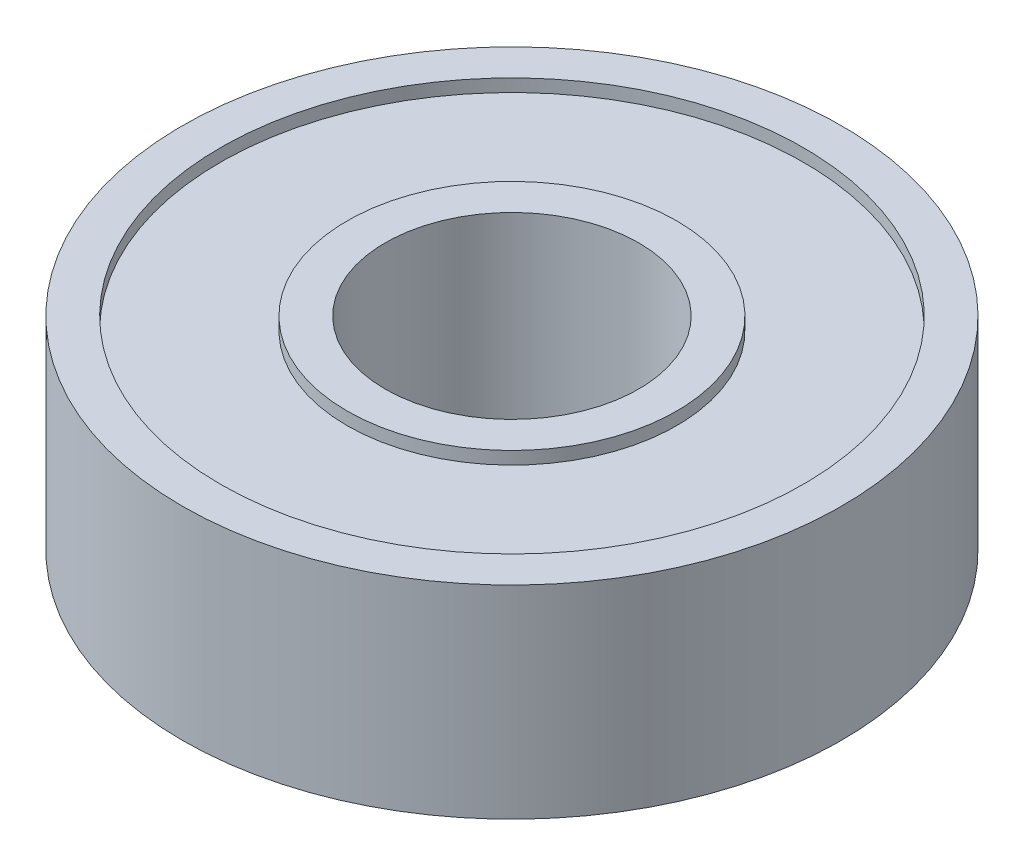
SolidWorks part; units mm, degrees
ref_plane "Plano frontal" through (0, 0, 0) normal (0, 0, 1) x (1, 0, 0)
ref_plane "Plano superior" through (0, 0, 0) normal (0, 1, 0) x (1, 0, 0)
ref_plane "Plano direito" through (0, 0, 0) normal (1, 0, 0) x (0, 0, -1)
sketch "Esboço1" plane through (0, 0, 0) normal (0, 0, 1) x (1, 0, 0)
  line L0 (0, 7.6011) -> (0, -6.5883) construction
  line L1 (5, 4) -> (6.5, 4)
  line L2 (5, 4) -> (5, -4)
  line L3 (5, -4) -> (6.5, -4)
  line L4 (6.5, 4) -> (6.5, -4)
  line L5 (11.5, 4) -> (13, 4)
  line L6 (11.5, 4) -> (11.5, -4)
  line L7 (11.5, -4) -> (13, -4)
  line L8 (13, 4) -> (13, -4)
  dimension "D1" = 13
  dimension "D2" = 5
  dimension "D3" = 1.5
  dimension "D4" = 1.5
  dimension "D5" = 8
  dimension "D6" = 4
revolve "Revolução1" add sketch "Esboço1" angle 360 about L0
sketch "Esboço4" plane through (0, 0, 0) normal (0, 0, 1) x (1, 0, 0)
  line L0 (-6.5, 3.5) -> (-11.5, 3.5)
  line L1 (-11.5, 3.5) -> (-11.5, -3.5)
  line L2 (-11.5, -3.5) -> (-6.5, -3.5)
  line L3 (-6.5, -3.5) -> (-6.5, 3.5)
  line L4 (11.5, 4) -> (-11.5, 4) construction
  line L5 (-11.5, -4) -> (11.5, -4) construction
  line L6 (0, 5.9823) -> (0, -6.2408) construction
  dimension "D1" = 6.5
  dimension "D2" = 11.5
  dimension "D3" = 0.5
  dimension "D4" = 0.5
revolve "Revolução2" add sketch "Esboço4" angle 360 about L6
